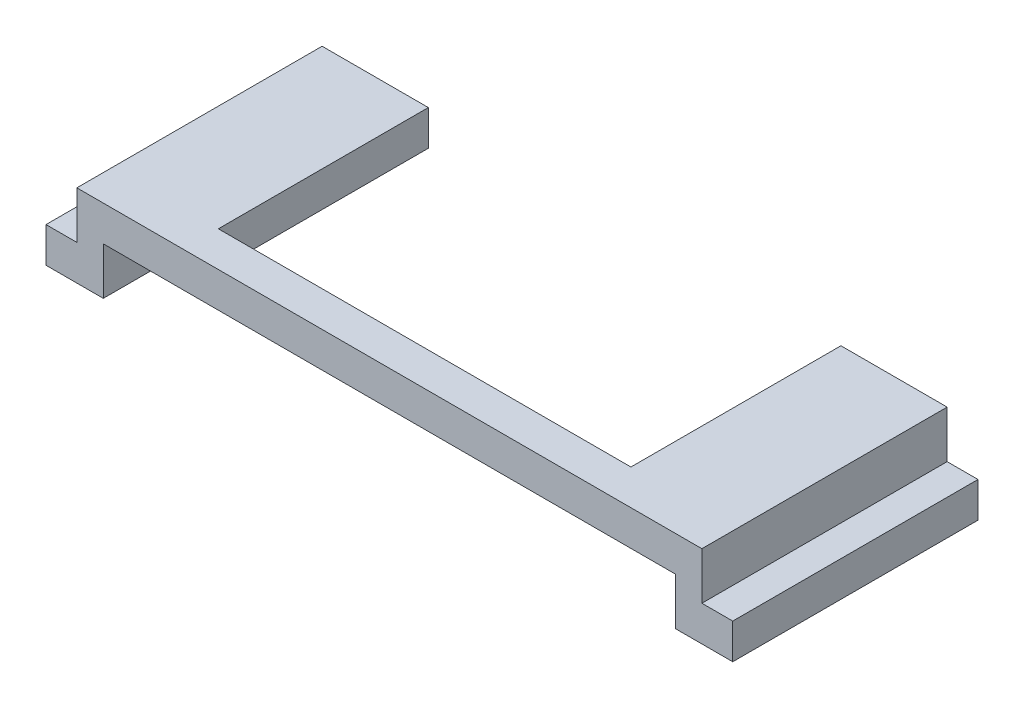
SolidWorks part; units mm, degrees
ref_plane "Front Plane" through (0, 0, 0) normal (0, 0, 1) x (1, 0, 0)
ref_plane "Top Plane" through (0, 0, 0) normal (0, 1, 0) x (1, 0, 0)
ref_plane "Right Plane" through (0, 0, 0) normal (1, 0, 0) x (0, 0, -1)
sketch "Sketch1" plane through (0, 0, 0) normal (0, 0, 1) x (1, 0, 0)
  line L8 (-19.475, -2.68) -> (-16.225, -2.68)
  line L9 (-16.225, -2.68) -> (-16.225, 0)
  line L10 (-16.225, 0) -> (16.225, 0)
  line L11 (16.225, 0) -> (16.225, -2.68)
  line L12 (16.225, -2.68) -> (19.475, -2.68)
  line L14 (-19.475, -2.68) -> (-19.475, -0.68)
  line L15 (-19.475, -0.68) -> (-17.725, -0.68)
  line L16 (-17.725, -0.68) -> (-17.725, 2)
  line L17 (-17.725, 2) -> (17.725, 2)
  line L18 (17.725, 2) -> (17.725, -0.68)
  line L19 (17.725, -0.68) -> (19.475, -0.68)
  line L20 (19.475, -0.68) -> (19.475, -2.68)
  point P6 (0, 0)
  point P7 (0, 0)
  point P15 (-11.4462, -0.5077)
  point P16 (0, 0)
  dimension "D1" = 2
  dimension "D2" = 1.5
  dimension "D3" = 32.45
  dimension "D4" = 2
  dimension "D5" = 2.68
  dimension "D6" = 1.75
extrude "Boss-Extrude1" add sketch "Sketch1" along normal blind 13.91
sketch "Sketch2" plane through (0, 2, 0) normal (0, 1, 0) x (1, 0, 0)
  line L0 (17.725, 0) -> (-17.725, 0) construction
  line L1 (-11.7, -11.91) -> (11.7, -11.91)
  line L2 (-11.7, -11.91) -> (-11.7, 0)
  line L3 (-11.7, 0) -> (11.7, 0)
  line L4 (11.7, -11.91) -> (11.7, 0)
  line L5 (-11.7, -11.91) -> (11.7, 0) construction
  line L6 (-11.7, 0) -> (11.7, -11.91) construction
  point P0 (0, -5.955)
  point P7 (2.9438, 0)
  point P8 (0, 0)
  dimension "D1" = 11.91
  dimension "D2" = 23.4
extrude "Cut-Extrude1" cut sketch "Sketch2" against normal up to next
